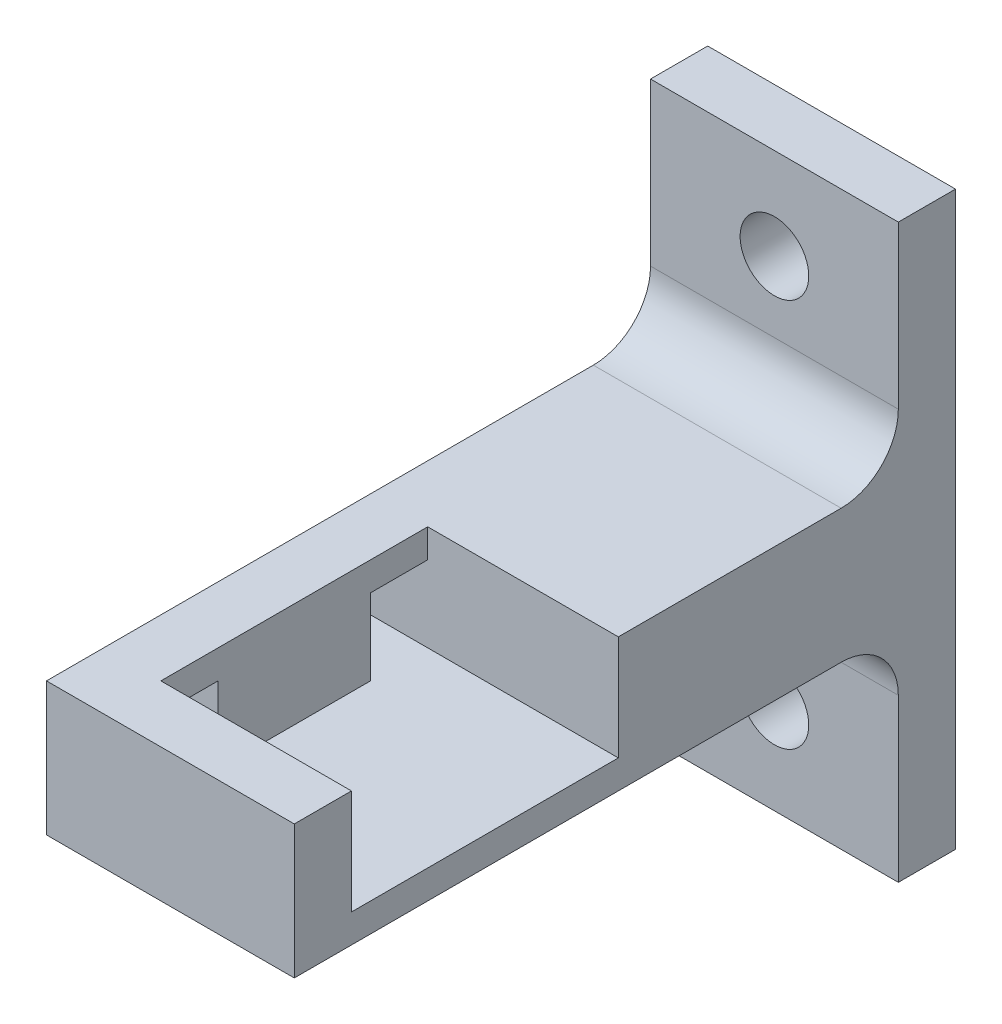
SolidWorks part; units mm, degrees
ref_plane "Front Plane" through (0, 0, 0) normal (0, 0, 1) x (1, 0, 0)
ref_plane "Top Plane" through (0, 0, 0) normal (0, 1, 0) x (1, 0, 0)
ref_plane "Right Plane" through (0, 0, 0) normal (1, 0, 0) x (0, 0, -1)
sketch "Sketch1" plane through (0, 0, 0) normal (0, 0, 1) x (1, 0, 0)
  line L0 (6.5, 30) -> (6.5, 25.2) construction
  line L1 (0, 0) -> (13, 0)
  line L2 (0, 0) -> (0, 30)
  line L3 (0, 30) -> (13, 30)
  line L4 (13, 0) -> (13, 30)
  line L5 (6.5, 25.2) -> (6.5, 4.8) construction
  line L6 (6.5, 4.8) -> (6.5, 0) construction
  circle A0 centre (6.5, 25.2) radius 1.8
  circle A1 centre (6.5, 4.8) radius 1.8
  dimension "D3" = 3.6
  dimension "D4" = 3
  dimension "D1" = 30
  dimension "D2" = 13
extrude "Boss-Extrude1" add sketch "Sketch1" along normal blind 3
sketch "Sketch2" plane through (0, 0, 3) normal (0, 0, 1) x (1, 0, 0)
  line L0 (0, 30) -> (0, 0) construction
  line L1 (0, 11.5) -> (13, 11.5)
  line L2 (0, 11.5) -> (0, 18.5)
  line L3 (0, 18.5) -> (13, 18.5)
  line L4 (13, 11.5) -> (13, 18.5)
  line L5 (13, 0) -> (13, 30) construction
  point P8 (0, 15)
  point P9 (0, 15)
  dimension "D1" = 7
extrude "Boss-Extrude2" add sketch "Sketch2" along normal blind 31.69
sketch "Sketch3" plane through (0, 18.5, 0) normal (0, 1, 0) x (1, 0, 0)
  line L0 (13, -34.69) -> (13, -3) construction
  line L1 (13, -31.69) -> (3, -31.69)
  line L2 (13, -31.69) -> (13, -17.69)
  line L3 (13, -17.69) -> (3, -17.69)
  line L4 (3, -31.69) -> (3, -17.69)
  line L5 (13, -34.69) -> (0, -34.69) construction
  dimension "D1" = 14
  dimension "D2" = 10
  dimension "D3" = 3
extrude "Cut-Extrude1" cut sketch "Sketch3" against normal blind 5.5
sketch "Sketch4" plane through (3, 0, 0) normal (1, 0, 0) x (0, 0, -1)
  line L0 (-31.69, 13) -> (-17.69, 13) construction
  line L1 (-31.69, 13) -> (-28.69, 13)
  line L2 (-31.69, 13) -> (-31.69, 17)
  line L3 (-31.69, 17) -> (-28.69, 17)
  line L4 (-28.69, 13) -> (-28.69, 17)
  line L5 (-20.69, 13) -> (-17.69, 13)
  line L6 (-20.69, 13) -> (-20.69, 17)
  line L7 (-20.69, 17) -> (-17.69, 17)
  line L8 (-17.69, 13) -> (-17.69, 17)
  line L9 (-17.69, 13) -> (-17.69, 18.5) construction
  dimension "D1" = 4
  dimension "D2" = 3
extrude "Cut-Extrude2" cut sketch "Sketch4" against normal through all
fillet "Fillet1" radius 3 2 edges
